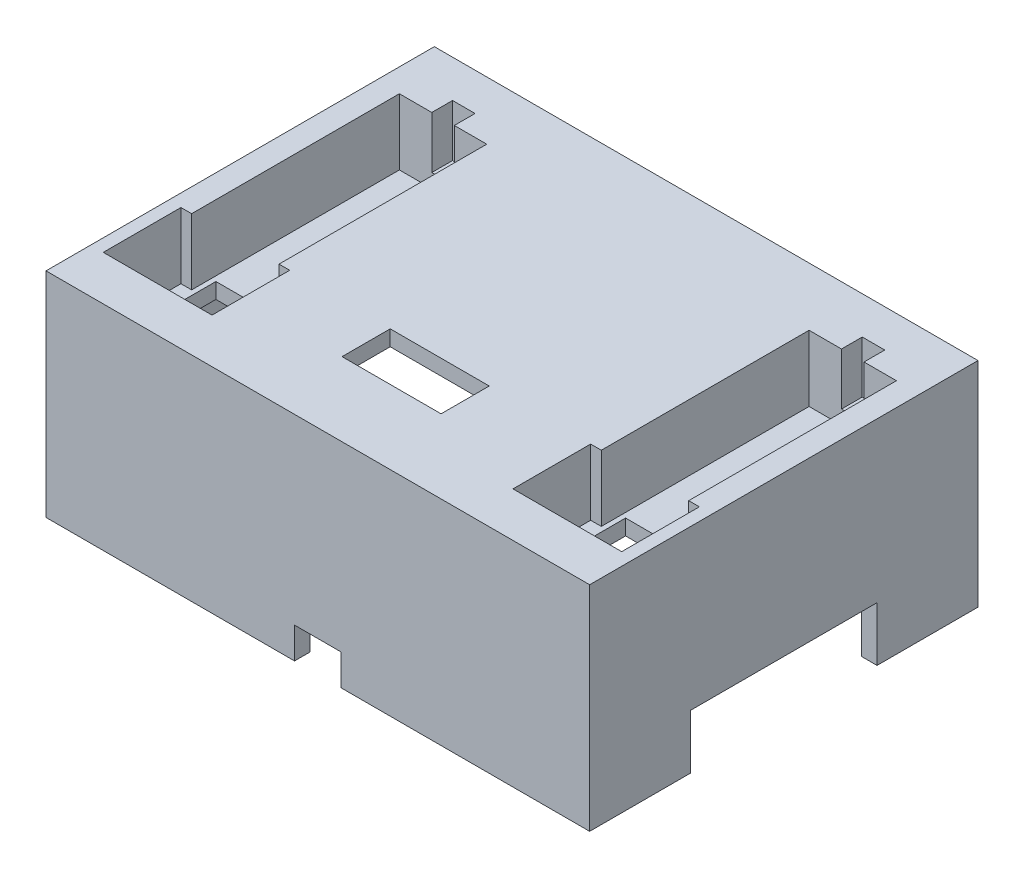
SolidWorks part; units mm, degrees
ref_plane "Front Plane" through (0, 0, 0) normal (0, 0, 1) x (1, 0, 0)
ref_plane "Top Plane" through (0, 0, 0) normal (0, 1, 0) x (1, 0, 0)
ref_plane "Right Plane" through (0, 0, 0) normal (1, 0, 0) x (0, 0, -1)
sketch "Sketch1" plane through (0, 0, 0) normal (0, 1, 0) x (1, 0, 0)
  line L1 (0, 0) -> (140, 0)
  line L2 (0, 0) -> (0, 100)
  line L3 (0, 100) -> (140, 100)
  line L4 (140, 0) -> (140, 100)
  dimension "D1" = 140
  dimension "D2" = 100
extrude "Boss-Extrude1" add sketch "Sketch1" along normal blind 55
sketch "Sketch2" plane through (0, 55, 0) normal (0, 1, 0) x (1, 0, 0)
  line L0 (70, 100) -> (70, 0) construction
  line L1 (6, 85) -> (28.5, 85)
  line L2 (6, 85) -> (6, 15)
  line L3 (6, 15) -> (28.5, 15)
  line L4 (28.5, 85) -> (28.5, 15)
  line L9 (140, 100) -> (0, 100) construction
  line L10 (0, 0) -> (140, 0) construction
  line L11 (0, 100) -> (0, 0) construction
  line L12 (134, 15) -> (111.5, 15)
  line L13 (111.5, 85) -> (111.5, 15)
  line L14 (134, 85) -> (111.5, 85)
  line L15 (134, 85) -> (134, 15)
  point P13 (0, 50)
  point P14 (6, 50)
  dimension "D1" = 22.5
  dimension "D2" = 70
  dimension "D3" = 6
extrude "Cut-Extrude1" cut sketch "Sketch2" against normal blind 17
sketch "Sketch3" plane through (0, 55, 0) normal (0, 1, 0) x (1, 0, 0)
  line L0 (28.5, 85) -> (6, 85) construction
  line L1 (14.35, 85) -> (20.15, 85)
  line L2 (14.35, 85) -> (14.35, 90.34)
  line L3 (14.35, 90.34) -> (20.15, 90.34)
  line L4 (20.15, 85) -> (20.15, 90.34)
  line L6 (6, 15) -> (28.5, 15) construction
  line L7 (70, 100) -> (70, 0) construction
  line L8 (140, 100) -> (0, 100) construction
  line L9 (0, 0) -> (140, 0) construction
  line L10 (125.65, 90.34) -> (119.85, 90.34)
  line L11 (119.85, 85) -> (119.85, 90.34)
  line L12 (125.65, 85) -> (119.85, 85)
  line L13 (125.65, 85) -> (125.65, 90.34)
  point P8 (17.25, 15)
  point P9 (17.25, 85)
  dimension "D1" = 5.34
  dimension "D2" = 5.8
extrude "Cut-Extrude2" cut sketch "Sketch3" against normal blind 13.4
sketch "Sketch4" plane through (0, 55, 0) normal (0, 1, 0) x (1, 0, 0)
  line L0 (6, 15) -> (28.5, 15) construction
  line L1 (3.25, 31.5) -> (31.25, 31.5)
  line L2 (3.25, 31.5) -> (3.25, 11.5)
  line L3 (3.25, 11.5) -> (31.25, 11.5)
  line L4 (31.25, 31.5) -> (31.25, 11.5)
  line L6 (70, 100) -> (70, 0) construction
  line L7 (140, 100) -> (0, 100) construction
  line L8 (0, 0) -> (140, 0) construction
  line L9 (136.75, 11.5) -> (108.75, 11.5)
  line L10 (108.75, 31.5) -> (108.75, 11.5)
  line L11 (136.75, 31.5) -> (108.75, 31.5)
  line L12 (136.75, 31.5) -> (136.75, 11.5)
  point P6 (17.25, 15)
  point P7 (17.25, 11.5)
  point P8 (31.25, 14.7638)
  dimension "D1" = 28
  dimension "D2" = 20
  dimension "D3" = 3.5
extrude "Cut-Extrude3" cut sketch "Sketch4" against normal up to surface (17 mm away) contours L2 L3 L4 L1 | L10 L9 L12 L11 up to face at (122.75, 38, -50)
shell "Shell1" thickness 4
sketch "Sketch5" plane through (0, 38, 0) normal (0, 1, 0) x (1, 0, 0)
  line L1 (7.25, 36.5) -> (27.25, 36.5)
  line L2 (7.25, 36.5) -> (7.25, 18.5)
  line L3 (7.25, 18.5) -> (27.25, 18.5)
  line L4 (27.25, 36.5) -> (27.25, 18.5)
  line L5 (70, 100) -> (70, 0) construction
  line L6 (140, 100) -> (0, 100) construction
  line L7 (0, 0) -> (140, 0) construction
  line L8 (132.75, 18.5) -> (112.75, 18.5)
  line L9 (112.75, 36.5) -> (112.75, 18.5)
  line L10 (132.75, 36.5) -> (112.75, 36.5)
  line L11 (132.75, 36.5) -> (132.75, 18.5)
  line L12 (3.25, 11.5) -> (31.25, 11.5) construction
  point P6 (17.25, 11.5)
  point P7 (17.25, 18.5)
  dimension "D1" = 20
  dimension "D2" = 18
  dimension "D3" = 7
extrude "Cut-Extrude4" cut sketch "Sketch5" against normal through all
sketch "Sketch6" plane through (0, 55, 0) normal (0, 1, 0) x (1, 0, 0)
  line L0 (140, 100) -> (0, 100) construction
  line L1 (57.25, 31.387) -> (82.75, 31.387)
  line L2 (57.25, 31.387) -> (57.25, 18.987)
  line L3 (57.25, 18.987) -> (82.75, 18.987)
  line L4 (82.75, 31.387) -> (82.75, 18.987)
  point P6 (70, 100)
  point P7 (70, 31.387)
  dimension "D1" = 25.5
  dimension "D2" = 12.4
extrude "Cut-Extrude5" cut sketch "Sketch6" against normal through all
sketch "Sketch7" plane through (0, 55, 0) normal (0, 1, 0) x (1, 0, 0)
  line L0 (56.5, 25.187) -> (83.5, 25.187) construction
  line L1 (140, 100) -> (0, 100) construction
  line L2 (57.25, 31.387) -> (57.25, 18.987) construction
  circle A0 centre (56.5, 25.187) radius 0.55
  circle A1 centre (83.5, 25.187) radius 0.55
  point P6 (70, 100)
  point P7 (70, 25.187)
  point P10 (57.25, 25.187)
  dimension "D1" = 1.1
  dimension "D2" = 1.1
  dimension "D3" = 27
sketch "Sketch8" plane through (0, 0, 0) normal (0, 0, 1) x (1, 0, 0)
  line L0 (0, 0) -> (140, 0) construction
  line L1 (64, 0) -> (76, 0)
  line L2 (64, 0) -> (64, 8)
  line L3 (64, 8) -> (76, 8)
  line L4 (76, 0) -> (76, 8)
  point P6 (70, 0)
  point P7 (70, 8)
  dimension "D1" = 8
  dimension "D2" = 12
sketch "Sketch9" plane through (140, 0, 0) normal (1, 0, 0) x (0, 0, -1)
  line L0 (0, 0) -> (100, 0) construction
  line L1 (26, 0) -> (74, 0)
  line L2 (26, 0) -> (26, 14)
  line L3 (26, 14) -> (74, 14)
  line L4 (74, 0) -> (74, 14)
  line L5 (0, 55) -> (100, 55) construction
  point P8 (50, 55)
  point P9 (50, 0)
  dimension "D1" = 14
  dimension "D2" = 48
extrude "Cut-Extrude6" cut sketch "Sketch9" against normal through all
extrude "Cut-Extrude7" cut sketch "Sketch8" against normal up to surface (4 mm away) up to face at (70, 25.5, -4)
